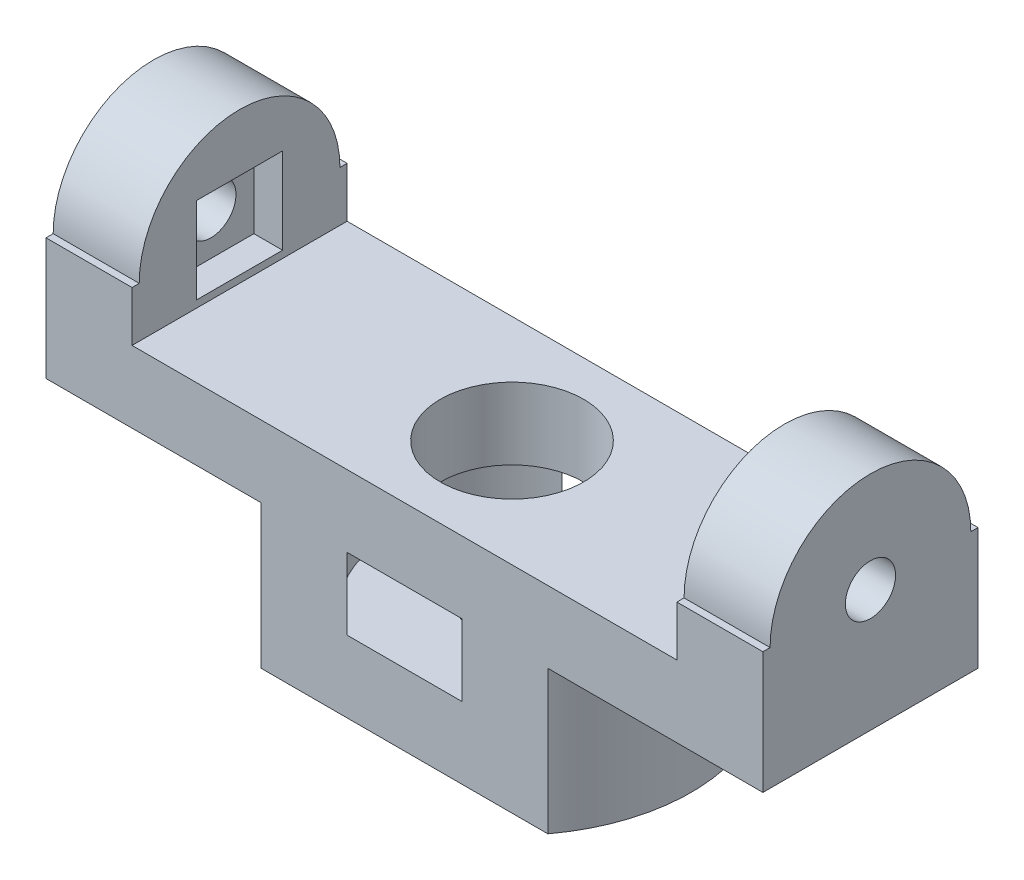
SolidWorks part; units mm, degrees
ref_plane "前视基准面" through (0, 0, 0) normal (0, 0, 1) x (1, 0, 0)
ref_plane "上视基准面" through (0, 0, 0) normal (0, 1, 0) x (1, 0, 0)
ref_plane "右视基准面" through (0, 0, 0) normal (1, 0, 0) x (0, 0, -1)
sketch "草图1" plane through (0, 0, 0) normal (0, 0, 1) x (1, 0, 0)
  line L12 (0, 0) -> (0, 16)
  line L13 (0, 16) -> (6, 16)
  line L14 (6, 16) -> (6, 5)
  line L20 (6, 5) -> (44, 5)
  line L21 (44, 5) -> (44, 16)
  line L22 (44, 16) -> (50, 16)
  line L23 (50, 16) -> (50, 0)
  line L28 (50, 0) -> (0, 0)
  line L29 (25, 5) -> (25, 0) construction
  point P2 (0, 0)
  point P6 (0, 0)
  point P9 (0, 0)
  dimension "D1" = 50
  dimension "D3" = 5
  dimension "D4" = 16
  dimension "D5" = 6
extrude "凸台-拉伸1" add sketch "草图1" along normal blind 15
sketch "草图3" plane through (50, 0, 0) normal (1, 0, 0) x (0, 0, -1)
  line L3 (-14.5, 8.5) -> (-23.0665, 8.5)
  line L4 (-23.0665, 8.5) -> (-23.0665, 64.3013)
  line L5 (-23.0665, 64.3013) -> (5.9064, 64.3013)
  line L6 (5.9064, 64.3013) -> (5.9064, 8.5)
  line L7 (5.9064, 8.5) -> (-0.5, 8.5)
  line L11 (-15, 0) -> (0, 0) construction
  line L12 (-7.5, 8.5) -> (-7.5, 0) construction
  arc A0 (-0.5, 8.5) -> (-14.5, 8.5) centre (-7.5, 8.5) ccw
  circle A1 centre (-7.5, 8.5) radius 1.75
  dimension "D1" = 3.5
  dimension "D2" = 8.5
  dimension "D3" = 7
extrude "切除-拉伸2" cut sketch "草图3" against normal through all
sketch "草图8" plane through (0, 0, 0) normal (0, -1, 0) x (1, 0, 0)
  line L0 (25, 15) -> (25, 7.5) construction
  line L1 (0, 15) -> (50, 15) construction
  line L2 (25, 7.5) -> (50, 7.5) construction
  line L3 (50, 15) -> (50, 0) construction
  line L4 (15, 15) -> (21, 15)
  line L5 (15, 0) -> (21, 0)
  line L6 (29, 15) -> (35, 15)
  line L7 (0, 0) -> (50, 0) construction
  line L8 (29, 0) -> (35, 0)
  arc A0 (15, 15) -> (15, 0) centre (25, 7.5) ccw
  arc A1 (35, 0) -> (35, 15) centre (25, 7.5) ccw
  arc A2 (21, 15) -> (21, 0) centre (25, 7.5) ccw
  arc A3 (29, 0) -> (29, 15) centre (25, 7.5) ccw
  dimension "D1" = 25
  dimension "D2" = 17
extrude "凸台-拉伸2" add sketch "草图8" along normal blind 10
sketch "草图9" plane through (0, -10, 0) normal (0, -1, 0) x (1, 0, 0)
  line L0 (21, 15) -> (29, 15)
  line L1 (29, 0) -> (21, 0)
  line L4 (15, 0) -> (21, 0)
  line L5 (21, 15) -> (15, 15)
  line L6 (15, 0) -> (21, 0)
  line L7 (21, 15) -> (15, 15)
  line L8 (35, 15) -> (29, 15)
  line L9 (29, 0) -> (35, 0)
  line L10 (35, 15) -> (29, 15)
  line L11 (29, 0) -> (35, 0)
  arc A2 (15, 15) -> (15, 0) centre (25, 7.5) ccw
  arc A3 (21, 15) -> (21, 0) centre (25, 7.5) ccw
  arc A4 (15, 15) -> (15, 0) centre (25, 7.5) ccw
  arc A6 (35, 0) -> (35, 15) centre (25, 7.5) ccw
  arc A7 (29, 0) -> (29, 15) centre (25, 7.5) ccw
  arc A8 (35, 0) -> (35, 15) centre (25, 7.5) ccw
  dimension "D1" = 0
  dimension "D2" = 0
extrude "凸台-拉伸3" add sketch "草图9" against normal blind 5
sketch "草图6" plane through (0, -10, 0) normal (0, -1, 0) x (1, 0, 0)
  line L0 (25, 15) -> (25, 7.5) construction
  line L1 (35, 15) -> (15, 15) construction
  line L2 (25, 7.5) -> (50, 7.5) construction
  line L3 (50, 15) -> (50, 0) construction
  circle A0 centre (25, 7.5) radius 2.75
  point P4 (0, 0)
  point P5 (25, 15)
  point P7 (0, 0)
  point P8 (0, 0)
  point P9 (36, 7.5)
  point P10 (0, 0)
  point P12 (0, 0)
  point P13 (50, 7.5)
  dimension "D1" = 5.5
extrude "切除-拉伸5" cut sketch "草图6" against normal up to surface (15 mm away) up to face at (25, 5, 7.5)
sketch "草图7" plane through (0, 5, 0) normal (0, 1, 0) x (1, 0, 0)
  circle A0 centre (25, -7.5) radius 5
  circle A2 centre (25, -7.5) radius 2.75 construction
  dimension "D1" = 10
extrude "切除-拉伸6" cut sketch "草图7" against normal up to surface (5 mm away) up to face at (22.25, 0, 7.5)
sketch "草图10" plane through (44, 0, 0) normal (-1, 0, 0) x (0, 0, 1)
  line L1 (4.5, 11.5) -> (10.5, 11.5)
  line L2 (4.5, 11.5) -> (4.5, 5.5)
  line L3 (4.5, 5.5) -> (10.5, 5.5)
  line L4 (10.5, 11.5) -> (10.5, 5.5)
  line L5 (4.5, 11.5) -> (10.5, 5.5) construction
  line L6 (4.5, 5.5) -> (10.5, 11.5) construction
  point P0 (7.5, 8.5)
  dimension "D1" = 6
  dimension "D2" = 6
extrude "切除-拉伸7" cut sketch "草图10" against normal blind 2
sketch "草图11" plane through (6, 0, 0) normal (1, 0, 0) x (0, 0, -1)
  line L1 (-10.5, 11.5) -> (-4.5, 11.5)
  line L2 (-10.5, 11.5) -> (-10.5, 5.5)
  line L3 (-10.5, 5.5) -> (-4.5, 5.5)
  line L4 (-4.5, 11.5) -> (-4.5, 5.5)
  line L5 (-10.5, 11.5) -> (-4.5, 5.5) construction
  line L6 (-10.5, 5.5) -> (-4.5, 11.5) construction
  point P0 (-7.5, 8.5)
  dimension "D1" = 6
  dimension "D2" = 6
extrude "切除-拉伸8" cut sketch "草图11" against normal blind 2
